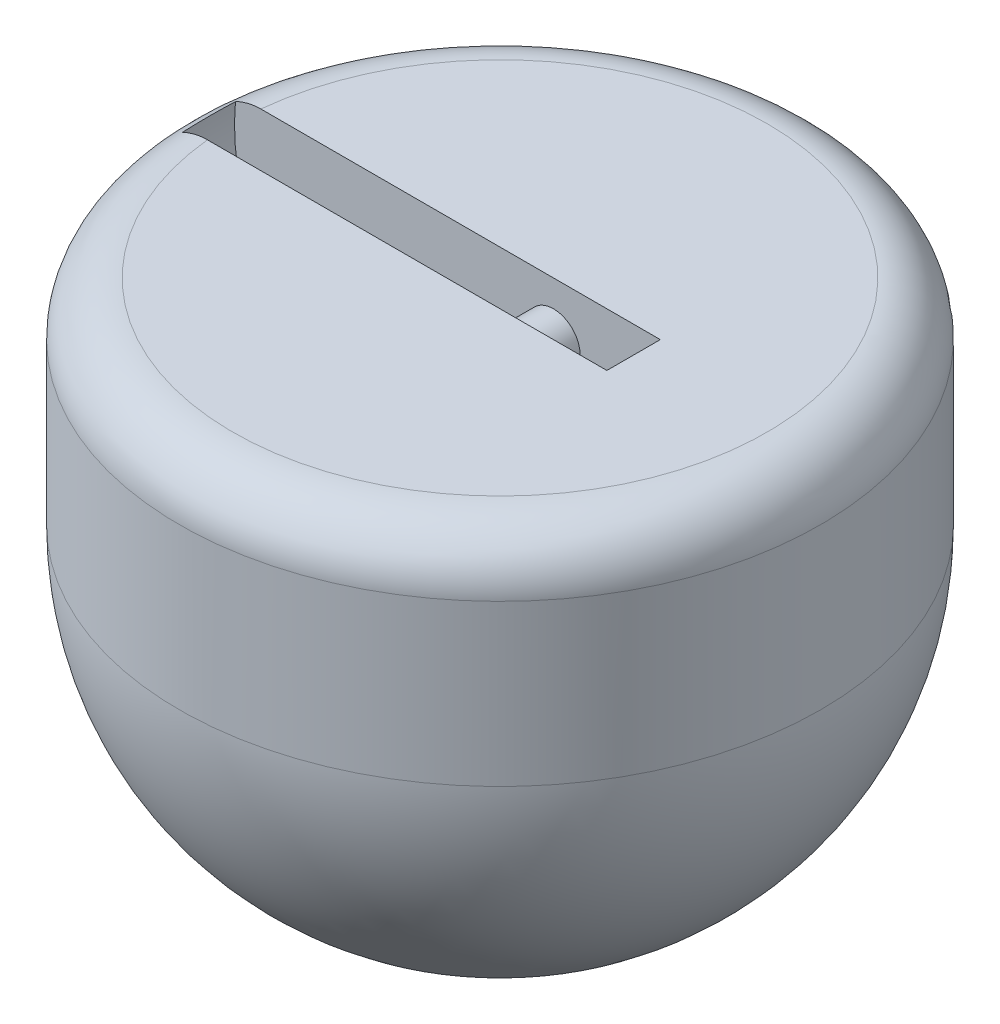
SolidWorks part; units mm, degrees
ref_plane "前视基准面" through (0, 0, 0) normal (0, 0, 1) x (1, 0, 0)
ref_plane "上视基准面" through (0, 0, 0) normal (0, 1, 0) x (1, 0, 0)
ref_plane "右视基准面" through (0, 0, 0) normal (1, 0, 0) x (0, 0, -1)
sketch "草图1" plane through (0, 0, 0) normal (0, 0, 1) x (1, 0, 0)
  line L0 (0, 0) -> (10, 0)
  line L1 (12, -2) -> (12, -8)
  line L2 (0, -20) -> (0, 0)
  arc A0 (10, 0) -> (12, -2) centre (10, -2) cw
  arc A1 (12, -8) -> (0, -20) centre (0, -8) cw
  dimension "D3" = 2
  dimension "D1" = 12
  dimension "D2" = 8
revolve "旋转1" add sketch "草图1" angle 360 about L2
sketch "草图2" plane through (0, 0, 0) normal (0, 0, 1) x (1, 0, 0)
  line L0 (10, 0) -> (-10, 0) construction
  line L1 (5, 0) -> (-10.8745, 0)
  arc A0 (5, 0) -> (-10.8745, 0) centre (-2.9373, -1) cw
  dimension "D1" = 8
  dimension "D2" = 1
  dimension "D3" = 5
extrude "切除-拉伸1" cut sketch "草图2" against normal mid plane 2
sketch "草图3" plane through (0, 0, 0) normal (0, 0, 1) x (1, 0, 0)
  line L0 (5, 0) -> (-9.9499, 0) construction
  circle A0 centre (1, -2) radius 1
  circle A1 centre (-3, -5) radius 1
  dimension "D1" = 2
  dimension "D2" = 2
  dimension "D3" = 4
  dimension "D4" = 3
  dimension "D5" = 1
extrude "凸台-拉伸1" add sketch "草图3" along normal mid plane 2
move or copy body "实体-移动/复制1" [suppressed] bodies to move or copy 108
move or copy body "实体-移动/复制2" [suppressed] bodies to move or copy 109 parameters "D1"=0, "D2"=0, "D3"=0
move or copy body "实体-移动/复制3" [suppressed] bodies to move or copy 110 parameters "D1"=0, "D2"=0, "D3"=0
